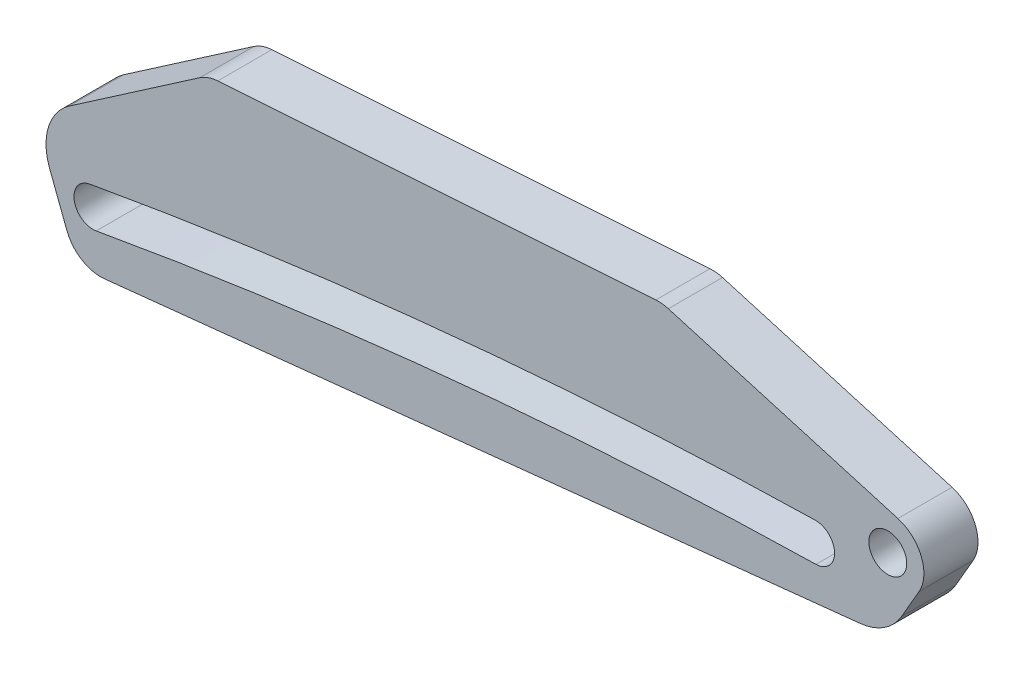
SolidWorks part; units mm, degrees
material "Thornel Mat VMA"
ref_plane "前视基准面" through (0, 0, 0) normal (0, 0, 1) x (1, 0, 0)
ref_plane "上视基准面" through (0, 0, 0) normal (0, 1, 0) x (1, 0, 0)
ref_plane "右视基准面" through (0, 0, 0) normal (1, 0, 0) x (0, 0, -1)
sketch "草图1" plane through (0, 0, 0) normal (0, 0, 1) x (1, 0, 0)
  line L1 (-49.8, -9.2342) -> (-51.6017, -5.5401)
  line L2 (-51.6017, -5.5401) -> (-37.6791, 4.0396)
  line L3 (-37.6791, 4.0396) -> (-12.5, 5.7255)
  line L4 (-12.5, 5.7255) -> (0.5595, 1.9201)
  line L5 (1.7321, -1) -> (0, -4)
  line L6 (0, -4) -> (-49.8, -9.2342)
  line L7 (0, 0) -> (0, -4) construction
  line L8 (0, 0) -> (9.997, 0) construction
  circle A0 centre (0, 0) radius 1.05
  arc A1 (1.7321, -1) -> (0.5595, 1.9201) centre (0, 0) ccw
  dimension "D1" = 2.1
  dimension "D2" = 4
  dimension "D3" = 4
  dimension "D4" = 6
  dimension "D5" = 49.8
  dimension "D6" = 110
  dimension "D7" = 4.11
  dimension "D8" = 16.9
  dimension "D9" = 98.531
  dimension "D10" = 149.3
  dimension "D11" = 12.5
extrude "凸台-拉伸1" add sketch "草图1" along normal blind 3
sketch "草图3" plane through (0, 0, 3) normal (0, 0, 1) x (1, 0, 0)
  arc A0 (-47, -6) -> (-4, -1.5) centre (1.4678, -261.4425) cw construction
  arc A1 (-4.0221, -0.4502) -> (-47.1957, -4.9684) centre (1.4678, -261.4425) ccw
  arc A2 (-3.9779, -2.5498) -> (-46.8043, -7.0316) centre (1.4678, -261.4425) ccw
  arc A3 (-3.9779, -2.5498) -> (-4.0221, -0.4502) centre (-4, -1.5) ccw
  arc A4 (-47.1957, -4.9684) -> (-46.8043, -7.0316) centre (-47, -6) ccw
  point P3 (-25.5937, -2.8547)
  dimension "D1" = 1.05
  dimension "D5" = 260
  dimension "D2" = 1.5
  dimension "D3" = 4
  dimension "D4" = 43
  dimension "D6" = 6
extrude "切除-拉伸1" cut sketch "草图3" against normal blind 3
sketch "草图5" plane through (0, 0, 3) normal (0, 0, 1) x (1, 0, 0)
  arc A0 (-44.2332, -4.424) -> (-43.8656, -6.4916) centre (-44.0494, -5.4578) ccw
  arc A1 (-47.1957, -4.9684) -> (-46.8043, -7.0316) centre (-47, -6) ccw construction
  arc A2 (-3.9779, -2.5498) -> (-46.8043, -7.0316) centre (1.4678, -261.4425) ccw construction
  arc A3 (-4.0221, -0.4502) -> (-47.1957, -4.9684) centre (1.4678, -261.4425) ccw construction
  arc A4 (-43.8656, -6.4916) -> (-46.8043, -7.0316) centre (1.4678, -261.4425) ccw
  arc A5 (-44.2332, -4.424) -> (-47.1957, -4.9684) centre (1.4678, -261.4425) ccw
  arc A6 (-47.1957, -4.9684) -> (-46.8043, -7.0316) centre (-47, -6) ccw
  dimension "D1" = 3
extrude "凸台-拉伸2" add sketch "草图5" against normal up to surface (3 mm away) up to face at (-25.5423, -3.3457, 0)
sketch "草图6" plane through (0, 0, 3) normal (0, 0, 1) x (1, 0, 0)
  line L0 (-47.297, -2.5782) -> (-44.9382, -8.7232)
  line L1 (-37.6791, 4.0396) -> (-51.6017, -5.5401) construction
  line L2 (-49.8, -9.2342) -> (0, -4) construction
  arc A0 (-44.2332, -4.424) -> (-43.8656, -6.4916) centre (-44.0494, -5.4578) ccw construction
  dimension "D1" = 2
  dimension "D2" = 105
extrude "切除-拉伸-薄壁1" cut sketch "草图6" against normal blind 3 and the other way through all thin
fillet "圆角1" radius 2 1 edges at (-44.9382, -8.7232, 1.5)
fillet "圆角2" radius 3 1 edges at (0, -4, 1.5)
fillet "圆角3" radius 3 1 edges at (-47.297, -2.5782, 1.5)
fillet "圆角4" radius 2 2 edges at (-12.5, 5.7255, 1.5) (-37.6791, 4.0396, 1.5)
